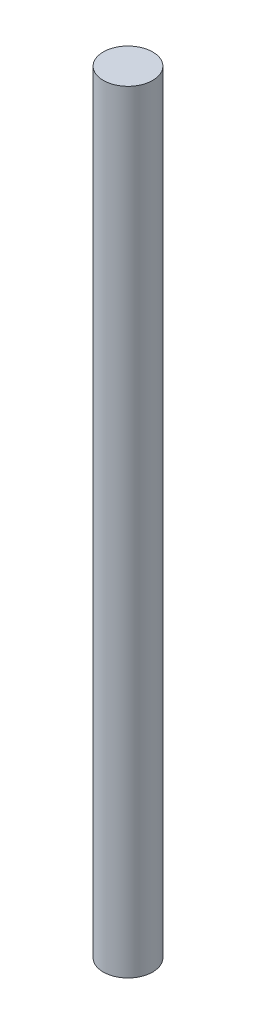
SolidWorks part; units mm, degrees
material "1.2343 (X38CrMoV5-1)"
ref_plane "Plano frontal" through (0, 0, 0) normal (0, 0, 1) x (1, 0, 0)
ref_plane "Plano superior" through (0, 0, 0) normal (0, 1, 0) x (1, 0, 0)
ref_plane "Plano direito" through (0, 0, 0) normal (1, 0, 0) x (0, 0, -1)
sketch "Esboço1" plane through (0, 0, 0) normal (0, 1, 0) x (1, 0, 0)
  circle A0 centre (0, 0) radius 4
  dimension "D1" = 8
extrude "Ressalto-extrusão1" add sketch "Esboço1" along normal up to surface (125.0994 mm away)
